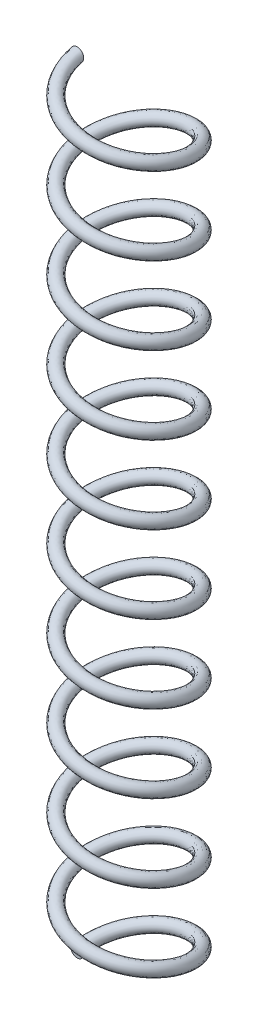
SolidWorks part; units mm, degrees
ref_plane "Plan de face" through (0, 0, 0) normal (0, 0, 1) x (1, 0, 0)
ref_plane "Plan de dessus" through (0, 0, 0) normal (0, 1, 0) x (1, 0, 0)
ref_plane "Plan de droite" through (0, 0, 0) normal (1, 0, 0) x (0, 0, -1)
sketch "Esquisse1" plane through (0, 0, 0) normal (0, 1, 0) x (1, 0, 0)
  circle A0 centre (0, 0) radius 4
  dimension "D1" = 8
curve "Hélice/Spirale1" pitch 6 height 60 turns 10
sketch "Esquisse2" plane through (0, 0, 0) normal (0, 0, 1) x (1, 0, 0)
  circle A0 centre (-4, 0) radius 0.5
  spline S0 degree 3 poles (-4, 0) (-4, 0.1242) (-3.7917, 0.3754) (-2.9021, 0.7499) (-1.5706, 1.125) (0, 1.5) (1.5706, 1.875) (2.9021, 2.25) (3.7917, 2.625) (4.1041, 3) (3.7917, 3.375) (2.9021, 3.75) (1.1268, 4.25) (-1.1268, 4.75) (-2.9021, 5.25) (-3.7917, 5.625) (-4.1041, 6) (-3.7917, 6.375) (-2.9021, 6.75) (-1.1268, 7.25) (1.1268, 7.75) (2.9021, 8.25) (3.7917, 8.625) (4.1041, 9) (3.7917, 9.375) (2.9021, 9.75) (1.1268, 10.25) (-1.1268, 10.75) (-2.9021, 11.25) (-3.7917, 11.625) (-4.1041, 12) (-3.7917, 12.375) (-2.9021, 12.75) (-1.1268, 13.25) (1.1268, 13.75) (2.9021, 14.25) (3.7917, 14.625) (4.1041, 15) (3.7917, 15.375) (2.9021, 15.75) (1.1268, 16.25) (-1.1268, 16.75) (-2.9021, 17.25) (-3.7917, 17.625) (-4.1041, 18) (-3.7917, 18.375) (-2.9021, 18.75) (-1.1268, 19.25) (1.1268, 19.75) (2.9021, 20.25) (3.7917, 20.625) (4.1041, 21) (3.7917, 21.375) (2.9021, 21.75) (1.1268, 22.25) (-1.1268, 22.75) (-2.9021, 23.25) (-3.7917, 23.625) (-4.1041, 24) (-3.7917, 24.375) (-2.9021, 24.75) (-1.1268, 25.25) (1.1268, 25.75) (2.9021, 26.25) (3.7917, 26.625) (4.1041, 27) (3.7917, 27.375) (2.9021, 27.75) (1.1268, 28.25) (-1.1268, 28.75) (-2.9021, 29.25) (-3.7917, 29.625) (-4.1041, 30) (-3.7917, 30.375) (-2.9021, 30.75) (-1.1268, 31.25) (1.1268, 31.75) (2.9021, 32.25) (3.7917, 32.625) (4.1041, 33) (3.7917, 33.375) (2.9021, 33.75) (1.1268, 34.25) (-1.1268, 34.75) (-2.9021, 35.25) (-3.7917, 35.625) (-4.1041, 36) (-3.7917, 36.375) (-2.9021, 36.75) (-1.1268, 37.25) (1.1268, 37.75) (2.9021, 38.25) (3.7917, 38.625) (4.1041, 39) (3.7917, 39.375) (2.9021, 39.75) (1.1268, 40.25) (-1.1268, 40.75) (-2.9021, 41.25) (-3.7917, 41.625) (-4.1041, 42) (-3.7917, 42.375) (-2.9021, 42.75) (-1.1268, 43.25) (1.1268, 43.75) (2.9021, 44.25) (3.7917, 44.625) (4.1041, 45) (3.7917, 45.375) (2.9021, 45.75) (1.1268, 46.25) (-1.1268, 46.75) (-2.9021, 47.25) (-3.7917, 47.625) (-4.1041, 48) (-3.7917, 48.375) (-2.9021, 48.75) (-1.1268, 49.25) (1.1268, 49.75) (2.9021, 50.25) (3.7917, 50.625) (4.1041, 51) (3.7917, 51.375) (2.9021, 51.75) (1.1268, 52.25) (-1.1268, 52.75) (-2.9021, 53.25) (-3.7917, 53.625) (-4.1041, 54) (-3.7917, 54.375) (-2.9021, 54.75) (-1.1268, 55.25) (1.1268, 55.75) (2.9021, 56.25) (3.7917, 56.625) (4.1041, 57) (3.7917, 57.375) (2.9021, 57.75) (1.5706, 58.125) (0, 58.5) (-1.5706, 58.875) (-2.9021, 59.2501) (-3.7917, 59.6246) (-4, 59.8758) (-4, 60) knots 0 0 0 0 0.00625 0.0125 0.01875 0.025 0.03125 0.0375 0.04375 0.05 0.05625 0.0625 0.06875 0.08125 0.0875 0.09375 0.1 0.10625 0.1125 0.11875 0.13125 0.1375 0.14375 0.15 0.15625 0.1625 0.16875 0.18125 0.1875 0.19375 0.2 0.20625 0.2125 0.21875 0.23125 0.2375 0.24375 0.25 0.25625 0.2625 0.26875 0.28125 0.2875 0.29375 0.3 0.30625 0.3125 0.31875 0.33125 0.3375 0.34375 0.35 0.35625 0.3625 0.36875 0.38125 0.3875 0.39375 0.4 0.40625 0.4125 0.41875 0.43125 0.4375 0.44375 0.45 0.45625 0.4625 0.46875 0.48125 0.4875 0.49375 0.5 0.50625 0.5125 0.51875 0.53125 0.5375 0.54375 0.55 0.55625 0.5625 0.56875 0.58125 0.5875 0.59375 0.6 0.60625 0.6125 0.61875 0.63125 0.6375 0.64375 0.65 0.65625 0.6625 0.66875 0.68125 0.6875 0.69375 0.7 0.70625 0.7125 0.71875 0.73125 0.7375 0.74375 0.75 0.75625 0.7625 0.76875 0.78125 0.7875 0.79375 0.8 0.80625 0.8125 0.81875 0.83125 0.8375 0.84375 0.85 0.85625 0.8625 0.86875 0.88125 0.8875 0.89375 0.9 0.90625 0.9125 0.91875 0.93125 0.9375 0.94375 0.95 0.95625 0.9625 0.96875 0.975 0.98125 0.9875 0.99375 1 1 1 1 construction
  dimension "D1" = 1
sweep "Balayage1" add profiles "Esquisse2" path "Hélice/Spirale1"
